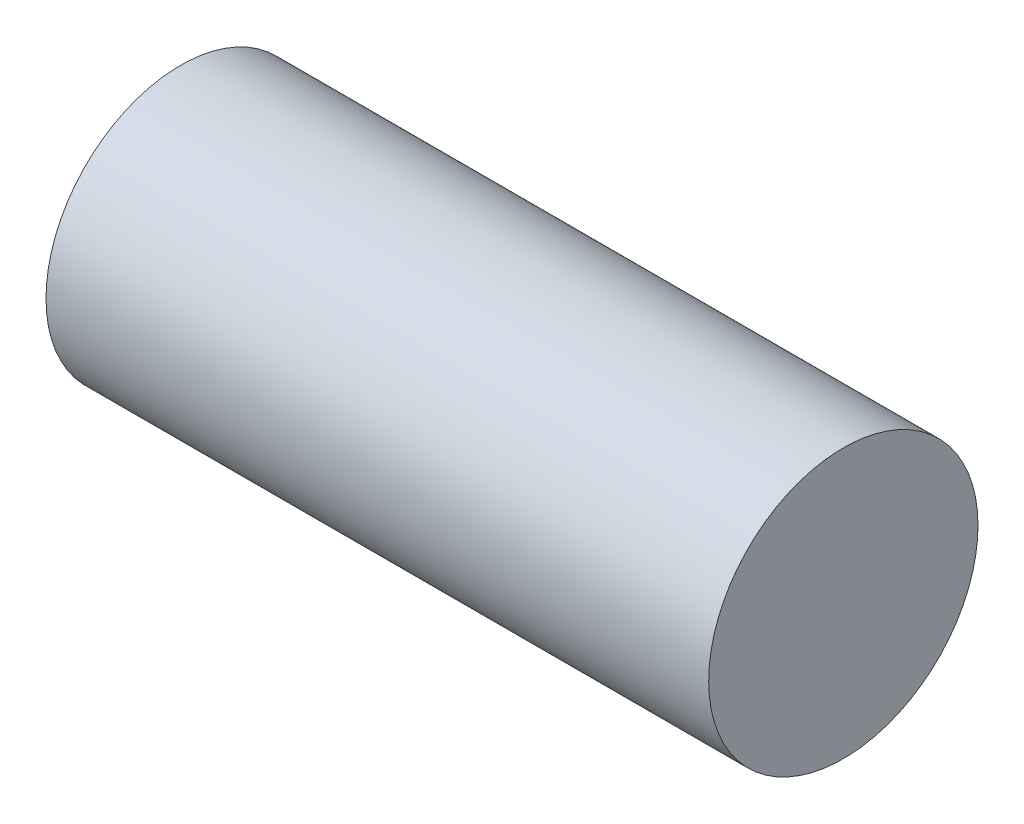
SolidWorks part; units mm, degrees
ref_plane "Front Plane" through (0, 0, 0) normal (0, 0, 1) x (1, 0, 0)
ref_plane "Top Plane" through (0, 0, 0) normal (0, 1, 0) x (1, 0, 0)
ref_plane "Right Plane" through (0, 0, 0) normal (1, 0, 0) x (0, 0, -1)
sketch "Sketch1" plane through (0, 0, 0) normal (1, 0, 0) x (0, 0, -1)
  circle A0 centre (0, 0) radius 30.48
  dimension "D1" = 60.96
extrude "Boss-Extrude2" add sketch "Sketch1" along normal blind 150 contours A0
